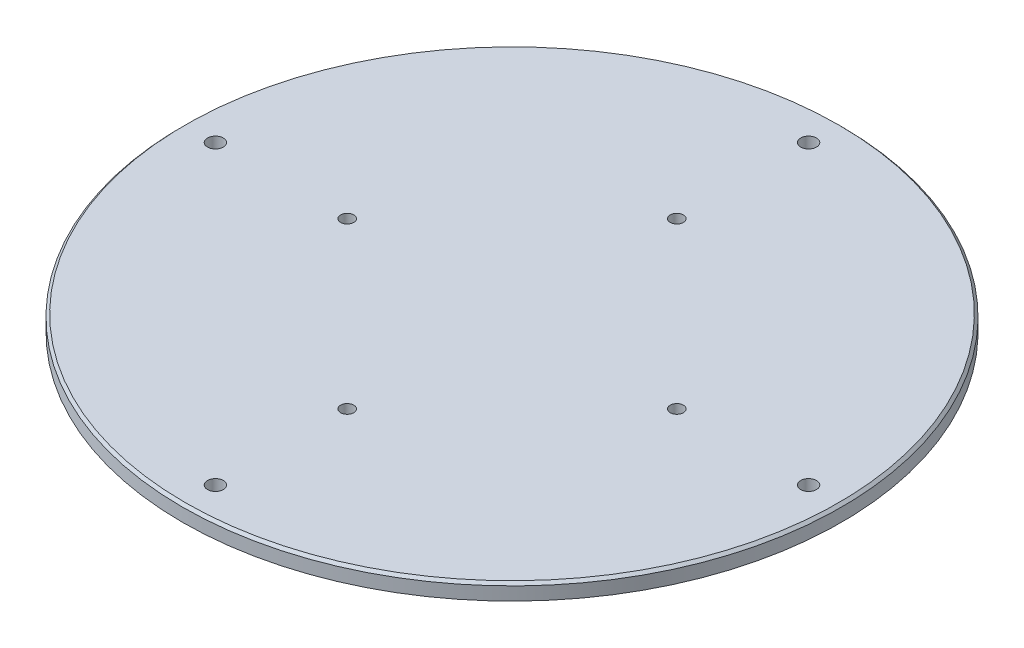
SolidWorks part; units mm, degrees
ref_plane "Спереди" through (0, 0, 0) normal (0, 0, 1) x (1, 0, 0)
ref_plane "Сверху" through (0, 0, 0) normal (0, 1, 0) x (1, 0, 0)
ref_plane "Справа" through (0, 0, 0) normal (1, 0, 0) x (0, 0, -1)
sketch "Эскиз1" plane through (0, 0, 0) normal (0, 1, 0) x (1, 0, 0)
  circle A0 centre (0, 0) radius 125
  dimension "D1" = 250
extrude "Бобышка-Вытянуть1" add sketch "Эскиз1" along normal blind 6
sketch "Эскиз3" plane through (0, 6, 0) normal (0, 1, 0) x (1, 0, 0)
  circle A0 centre (0, 0) radius 112.5 construction
  circle A1 centre (0, 112.5) radius 3
  circle A2 centre (-112.5, 0) radius 3
  circle A3 centre (0, -112.5) radius 3
  circle A4 centre (112.5, 0) radius 3
  dimension "D1" = 225
  dimension "D2" = 6
  dimension "D3" = 6
  dimension "D4" = 6
  dimension "D5" = 6
extrude "Вырез-Вытянуть2" cut sketch "Эскиз3" against normal blind 10
sketch "Эскиз4" plane through (0, 0, 0) normal (0, -1, 0) x (1, 0, 0)
  line L0 (0, 62.5) -> (0, -62.5) construction
  line L1 (0, -62.5) -> (62.5, 0) construction
  line L2 (62.5, 0) -> (-62.5, 0) construction
  circle A0 centre (0, 0) radius 62.5 construction
  circle A1 centre (0, 62.5) radius 2.5
  circle A2 centre (0, -62.5) radius 2.5
  circle A3 centre (62.5, 0) radius 2.5
  circle A4 centre (-62.5, 0) radius 2.5
  dimension "D1" = 125
  dimension "D2" = 5
  dimension "D3" = 5
  dimension "D4" = 5
  dimension "D5" = 5
extrude "Вырез-Вытянуть3" cut sketch "Эскиз4" against normal blind 10
chamfer "Фаска1" distance 1 angle 45 1 edges at (0, 6, 125)
